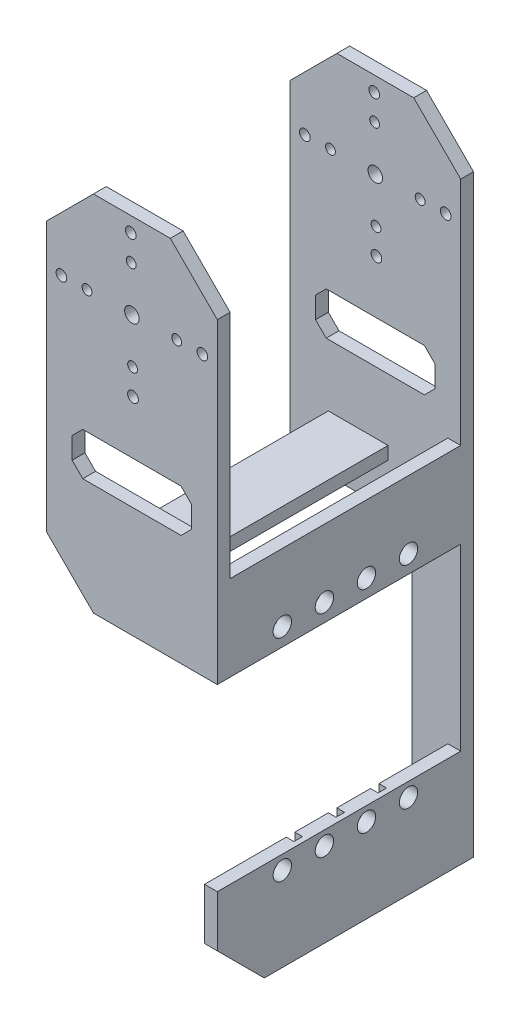
SolidWorks part; units mm, degrees
ref_plane "前视基准面" through (0, 0, 0) normal (0, 0, 1) x (1, 0, 0)
ref_plane "上视基准面" through (0, 0, 0) normal (0, 1, 0) x (1, 0, 0)
ref_plane "右视基准面" through (0, 0, 0) normal (1, 0, 0) x (0, 0, -1)
sketch "草图1" plane through (0, 0, 0) normal (0, 0, 1) x (1, 0, 0)
  line L1 (-20, -30) -> (20, -30)
  line L2 (-20, -30) -> (-20, 30)
  line L3 (-20, 30) -> (20, 30)
  line L4 (20, -30) -> (20, 30)
  line L5 (-20, -30) -> (20, 30) construction
  line L6 (-20, 30) -> (20, -30) construction
  point P0 (0, 0)
  dimension "D1" = 40
  dimension "D2" = 60
extrude "凸台-拉伸1" add sketch "草图1" along normal mid plane 60
chamfer "倒角3" distance 11 angle 45 2 edges at (20, 30, 0) (-20, 30, 0)
sketch "草图6" plane through (0, 30, 0) normal (0, 1, 0) x (1, 0, 0)
  line L0 (20, 30) -> (20, -30) construction
  line L1 (-20, -27) -> (20, -27)
  line L2 (-20, -27) -> (-20, 27)
  line L3 (-20, 27) -> (20, 27)
  line L4 (20, -27) -> (20, 27)
  line L5 (-20, -27) -> (20, 27) construction
  line L6 (-20, 27) -> (20, -27) construction
  line L7 (9, 30) -> (-9, 30) construction
  point P0 (0, 0)
  dimension "D1" = 3
extrude "切除-拉伸4" cut sketch "草图6" against normal blind 80
sketch "草图7" plane through (0, 0, 30) normal (0, 0, 1) x (1, 0, 0)
  line L0 (9, 30) -> (-9, 30) construction
  circle A0 centre (0, 10) radius 1.7
  dimension "D1" = 3.4
  dimension "D2" = 20
extrude "切除-拉伸5" cut sketch "草图7" against normal blind 80
sketch "草图9" plane through (0, 0, 30) normal (0, 0, 1) x (1, 0, 0)
  circle A0 centre (-16.498, 9.7403) radius 1.25
  circle A1 centre (-10.4987, 9.8347) radius 1.15
  circle A2 centre (-0.1653, 20.4987) radius 1.15
  circle A3 centre (-0.2597, 26.498) radius 1.25
  circle A4 centre (10.4987, 10.1653) radius 1.15
  circle A5 centre (16.498, 10.2597) radius 1.25
  circle A6 centre (0.1653, -0.4987) radius 1.15
  circle A7 centre (0.2597, -6.498) radius 1.25
  circle A8 centre (0, 10) radius 1.7 construction
  point P21 (0, 10)
  dimension "D2" = 2.5
  dimension "D3" = 2.3
  dimension "D1" = 4
extrude "切除-拉伸6" cut sketch "草图9" against normal blind 80
sketch "草图10" plane through (0, -30, 0) normal (0, -1, 0) x (1, 0, 0)
  line L1 (-20, 30) -> (20, 30)
  line L2 (-20, 30) -> (-20, 27)
  line L3 (-20, 27) -> (20, 27)
  line L4 (20, 30) -> (20, 27)
  line L5 (-20, -27) -> (20, -27)
  line L6 (-20, -27) -> (-20, -30)
  line L7 (-20, -30) -> (20, -30)
  line L8 (20, -27) -> (20, -30)
extrude "凸台-拉伸2" add sketch "草图10" along normal blind 90
sketch "草图11" plane through (0, 0, -27) normal (0, 0, 1) x (1, 0, 0)
  line L1 (20, -35) -> (17, -35)
  line L2 (20, -35) -> (20, -55)
  line L3 (20, -55) -> (17, -55)
  line L4 (17, -35) -> (17, -55)
  circle A0 centre (0, 10) radius 1.7 construction
  dimension "D3" = 45
  dimension "D1" = 20
  dimension "D2" = 3
extrude "凸台-拉伸3" add sketch "草图11" along normal up to surface (54 mm away) up to face at (-15.248, 9.7403, 27)
sketch "草图13" plane through (0, 0, -27) normal (0, 0, 1) x (1, 0, 0)
  line L1 (20, -120) -> (17, -120)
  line L2 (20, -120) -> (20, -92.3)
  line L3 (20, -92.3) -> (17, -92.3)
  line L4 (17, -120) -> (17, -92.3)
  dimension "D1" = 3
  dimension "D2" = 37.3
extrude "凸台-拉伸4" add sketch "草图13" along normal up to surface (54 mm away) up to face at (-15.248, 9.7403, 27)
sketch "草图12" plane through (20, 0, 0) normal (1, 0, 0) x (0, 0, -1)
  line L1 (-27, -55) -> (27, -55) construction
  line L2 (0, 24.7233) -> (0, -24.7233) construction
  circle A0 centre (-14.775, -50.85) radius 2.15
  circle A1 centre (-4.925, -50.85) radius 2.15
  circle A4 centre (-14.775, -100.27) radius 2.15
  circle A5 centre (-4.925, -100.27) radius 2.15
  circle A6 centre (4.925, -100.27) radius 2.15
  circle A7 centre (14.775, -100.27) radius 2.15
  circle A8 centre (4.925, -50.85) radius 2.15
  circle A9 centre (14.775, -50.85) radius 2.15
  dimension "D1" = 9.85
  dimension "D2" = 4.3
  dimension "D3" = 4.3
  dimension "D4" = 4.3
  dimension "D5" = 4.15
  dimension "D6" = 49.42
  dimension "D7" = 9.85
  dimension "D8" = 4.3
extrude "切除-拉伸7" cut sketch "草图12" against normal blind 10
sketch "草图15" plane through (0, 0, -27) normal (0, 0, 1) x (1, 0, 0)
  line L1 (20, -55) -> (-20, -55)
  line L2 (20, -55) -> (20, -97)
  line L3 (20, -97) -> (-20, -97)
  line L4 (-20, -55) -> (-20, -97)
  dimension "D1" = 40
  dimension "D2" = 42
extrude "切除-拉伸8" cut sketch "草图15" along normal blind 80
sketch "草图16" plane through (0, 0, 27) normal (0, 0, -1) x (-1, 0, 0)
  line L1 (-17, -97) -> (20, -97)
  line L2 (-17, -97) -> (-17, -120)
  line L3 (-17, -120) -> (20, -120)
  line L4 (20, -97) -> (20, -120)
extrude "切除-拉伸9" cut sketch "草图16" against normal blind 40
sketch "草图17" plane through (17, 0, 0) normal (-1, 0, 0) x (0, 0, 1)
  line L0 (-4.925, -50.85) -> (4.925, -50.85) construction
  line L1 (27, -55) -> (-27, -55) construction
  line L2 (-1, -46.7) -> (1, -46.7)
  line L3 (-1, -46.7) -> (-1, -55)
  line L4 (-1, -55) -> (1, -55)
  line L5 (1, -46.7) -> (1, -55)
  line L6 (-1, -46.7) -> (1, -55) construction
  line L7 (-1, -55) -> (1, -46.7) construction
  line L8 (-14.775, -50.85) -> (-4.925, -50.85) construction
  line L9 (0, -24.7233) -> (0, 24.7233) construction
  line L10 (-10.85, -46.7) -> (-8.85, -46.7)
  line L11 (-10.85, -46.7) -> (-10.85, -55)
  line L12 (-10.85, -55) -> (-8.85, -55)
  line L13 (-8.85, -46.7) -> (-8.85, -55)
  line L14 (-10.85, -46.7) -> (-8.85, -55) construction
  line L15 (-10.85, -55) -> (-8.85, -46.7) construction
  line L16 (10.85, -55) -> (8.85, -46.7) construction
  line L17 (10.85, -46.7) -> (8.85, -55) construction
  line L18 (8.85, -46.7) -> (8.85, -55)
  line L19 (10.85, -55) -> (8.85, -55)
  line L20 (10.85, -46.7) -> (10.85, -55)
  line L21 (10.85, -46.7) -> (8.85, -46.7)
  line L22 (-27, -55) -> (-27, -97) construction
  line L23 (-27, -120) -> (-27, 19) construction
  line L24 (-27, -35) -> (-27, -55) construction
  line L25 (-27, -76) -> (29.9811, -76) construction
  line L26 (10.85, -105.3) -> (8.85, -97) construction
  line L27 (10.85, -97) -> (8.85, -105.3) construction
  line L28 (-10.85, -97) -> (-8.85, -105.3) construction
  line L29 (-10.85, -105.3) -> (-8.85, -97) construction
  line L30 (-14.775, -101.15) -> (-4.925, -101.15) construction
  line L31 (-1, -97) -> (1, -105.3) construction
  line L32 (-1, -105.3) -> (1, -97) construction
  line L33 (-4.925, -101.15) -> (4.925, -101.15) construction
  line L34 (10.85, -105.3) -> (8.85, -105.3)
  line L35 (10.85, -105.3) -> (10.85, -97)
  line L36 (10.85, -97) -> (8.85, -97)
  line L37 (8.85, -105.3) -> (8.85, -97)
  line L38 (-8.85, -105.3) -> (-8.85, -97)
  line L39 (-10.85, -97) -> (-8.85, -97)
  line L40 (-10.85, -105.3) -> (-10.85, -97)
  line L41 (-10.85, -105.3) -> (-8.85, -105.3)
  line L42 (1, -105.3) -> (1, -97)
  line L43 (-1, -97) -> (1, -97)
  line L44 (-1, -105.3) -> (-1, -97)
  line L45 (-1, -105.3) -> (1, -105.3)
  point P4 (0, -50.85)
  point P12 (-9.85, -50.85)
  point P24 (9.85, -50.85)
  point P49 (9.85, -101.15)
  point P50 (-9.85, -101.15)
  point P51 (0, -101.15)
  dimension "D1" = 2
  dimension "D2" = 2
extrude "切除-拉伸10" cut sketch "草图17" against normal blind 1.8
sketch "草图18" plane through (17, 0, 0) normal (-1, 0, 0) x (0, 0, 1)
  line L0 (27, -35) -> (27, -55) construction
  line L1 (-27, -46.5) -> (27, -46.5)
  line L2 (-27, -46.5) -> (-27, -43.5)
  line L3 (-27, -43.5) -> (27, -43.5)
  line L4 (27, -46.5) -> (27, -43.5)
  line L5 (-27, -46.5) -> (27, -43.5) construction
  line L6 (-27, -43.5) -> (27, -46.5) construction
  point P0 (0, -45)
  dimension "D1" = 3
  dimension "D2" = 45
extrude "凸台-拉伸5" add sketch "草图18" along normal blind 28
sketch "草图19" plane through (0, -43.5, 0) normal (0, 1, 0) x (1, 0, 0)
  line L0 (-9, -27) -> (9, -27) construction
  line L1 (17, 27) -> (3, 27)
  line L2 (17, 27) -> (17, -27)
  line L3 (17, -27) -> (3, -27)
  line L4 (3, 27) -> (3, -27)
  dimension "D1" = 14
extrude "切除-拉伸11" cut sketch "草图19" against normal blind 11.5
chamfer "倒角4" distance 11 angle 45 3 edges at (-20, -120, -28.5) (-20, -55, 28.5) (18.5, -120, 30)
sketch "草图23" plane through (0, 0, -27) normal (0, 0, 1) x (1, 0, 0)
  line L0 (-20, -109) -> (-20, 19) construction
  line L1 (-20, -77) -> (-17, -77)
  line L2 (-20, -77) -> (-20, -95)
  line L3 (-20, -95) -> (-17, -95)
  line L4 (-17, -77) -> (-17, -95)
  point P6 (-20, -86)
  dimension "D1" = 3
  dimension "D2" = 18
  dimension "D3" = 14
sketch "草图24" plane through (0, 0, -27) normal (0, 0, 1) x (1, 0, 0)
  line L0 (-20, -109) -> (-20, 19) construction
  circle A0 centre (-14, -79) radius 1.7
  circle A1 centre (-14, -89) radius 1.7
  dimension "D1" = 3.4
  dimension "D2" = 3.4
  dimension "D3" = 10
  dimension "D4" = 6
  dimension "D5" = 20
extrude "切除-拉伸12" cut sketch "草图24" against normal blind 35
sketch "草图25" plane through (0, 0, -27) normal (0, 0, 1) x (1, 0, 0)
  line L0 (17, -120) -> (-9, -120) construction
  line L1 (17, -97) -> (17, -120) construction
  circle A0 centre (3, -116) radius 1.65
  circle A1 centre (13, -116) radius 1.65
  dimension "D1" = 3.3
  dimension "D2" = 4
  dimension "D3" = 14
  dimension "D4" = 10
  dimension "D5" = 3.3
extrude "切除-拉伸13" cut sketch "草图25" against normal blind 35
sketch "草图27" plane through (0, 0, -30) normal (0, 0, -1) x (-1, 0, 0)
  line L0 (-14, -21.5) -> (-11.5, -19)
  line L1 (-11.5, -29) -> (11.5, -29)
  line L2 (-14, -26.5) -> (-14, -21.5)
  line L3 (-11.5, -19) -> (11.5, -19)
  line L4 (14, -26.5) -> (14, -21.5)
  line L5 (-14, -29) -> (14, -19) construction
  line L6 (-14, -19) -> (14, -29) construction
  line L7 (-14, -26.5) -> (-11.5, -29)
  line L8 (11.5, -29) -> (14, -26.5)
  line L9 (11.5, -19) -> (14, -21.5)
  point P0 (0, -24)
  dimension "D1" = 28
  dimension "D2" = 10
  dimension "D3" = 24
extrude "切除-拉伸14" cut sketch "草图27" against normal blind 65
sketch "草图28" plane through (0, 0, -30) normal (0, 0, -1) x (-1, 0, 0)
  line L0 (-20, -120) -> (-20, 19) construction
  line L1 (-4, -105) -> (-1, -105)
  line L2 (-7, -102) -> (-7, -84)
  line L3 (-4, -81) -> (-1, -81)
  line L4 (-1, -105) -> (-1, -81)
  line L5 (-7, -105) -> (-1, -81) construction
  line L6 (-7, -81) -> (-1, -105) construction
  line L7 (7.5, -70) -> (9.5, -70)
  line L8 (7.5, -70) -> (7.5, -48)
  line L9 (7.5, -48) -> (9.5, -48)
  line L10 (12.5, -67) -> (12.5, -51)
  line L11 (7.5, -70) -> (12.5, -48) construction
  line L12 (7.5, -48) -> (12.5, -70) construction
  line L13 (20, 19) -> (20, -109) construction
  line L14 (9, -120) -> (-20, -120) construction
  line L15 (-7, -102) -> (-4, -105)
  line L16 (-7, -84) -> (-4, -81)
  line L17 (9.5, -48) -> (12.5, -51)
  line L18 (9.5, -70) -> (12.5, -67)
  point P0 (-4, -93)
  point P5 (10, -59)
  dimension "D1" = 16
  dimension "D2" = 6
  dimension "D3" = 10
  dimension "D4" = 15
  dimension "D5" = 50
  dimension "D6" = 5
  dimension "D7" = 24
  dimension "D8" = 22
extrude "切除-拉伸15" cut sketch "草图28" against normal blind 45
sketch "草图29" plane through (0, 0, -27) normal (0, 0, 1) x (1, 0, 0)
  line L0 (17, -120) -> (-9, -120) construction
  line L1 (8.5508, -120) -> (-24.9514, -120)
  line L2 (8.5508, -120) -> (8.5508, -56.6132)
  line L3 (8.5508, -56.6132) -> (-24.9514, -56.6132)
  line L4 (-24.9514, -120) -> (-24.9514, -56.6132)
extrude "切除-拉伸16" cut sketch "草图29" against normal blind 10
